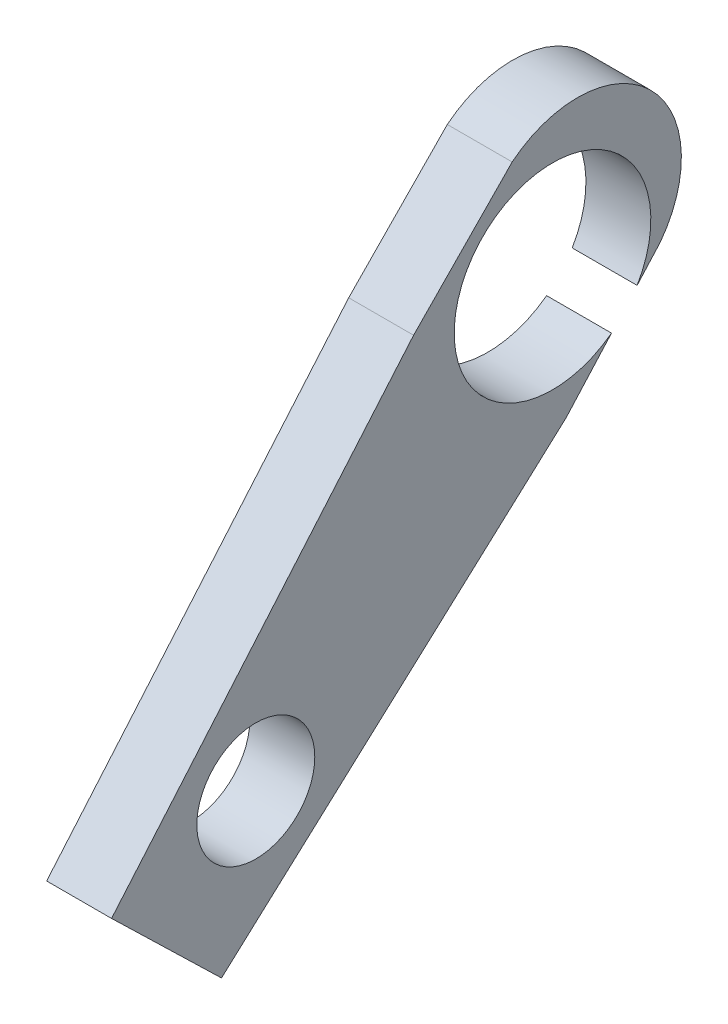
SolidWorks part; units mm, degrees
ref_plane "Front Plane" through (0, 0, 0) normal (0, 0, 1) x (1, 0, 0)
ref_plane "Top Plane" through (0, 0, 0) normal (0, 1, 0) x (1, 0, 0)
ref_plane "Right Plane" through (0, 0, 0) normal (1, 0, 0) x (0, 0, -1)
sketch "Sketch1" plane through (0, 0, 0) normal (1, 0, 0) x (0, 0, -1)
  line L0 (-175.561, 254.7808) -> (-150.6317, 230.6229)
  line L1 (-150.6317, 230.6229) -> (-72.5025, 301.5524)
  line L2 (-72.5025, 301.5524) -> (-51.1432, 325.3626)
  line L3 (-175.561, 254.7808) -> (-107.0773, 335.0577)
  line L4 (-107.0773, 335.0577) -> (-84.7235, 357.9043)
  arc A0 (-84.7235, 357.9043) -> (-51.1432, 325.3626) centre (-69.9156, 339.5879) cw
  circle A1 centre (-75.5764, 330.8703) radius 22.2928
  circle A2 centre (-142.8532, 263.4704) radius 13.373
  point P3 (-53.4777, 356.4567)
  point P8 (-75.5764, 330.8703)
  point P11 (-97.8245, 332.2808)
  point P14 (-156.2245, 263.2603)
extrude "Boss-Extrude1" add sketch "Sketch1" along normal blind 14.7135 contours A1 L2 A0 L4 L3 L0 L1 A2
move or copy body "Body-Move/Copy1" [suppressed] bodies to move or copy 101
